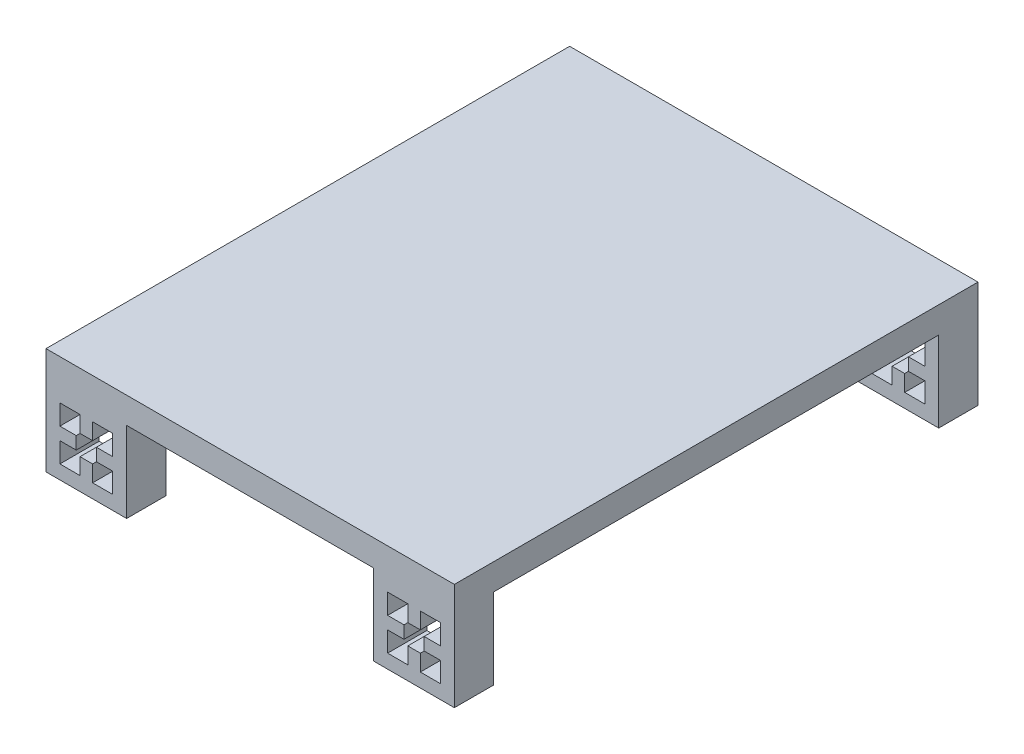
SolidWorks part; units mm, degrees
ref_plane "Plan de face" through (0, 0, 0) normal (0, 0, 1) x (1, 0, 0)
ref_plane "Plan de dessus" through (0, 0, 0) normal (0, 1, 0) x (1, 0, 0)
ref_plane "Plan de droite" through (0, 0, 0) normal (1, 0, 0) x (0, 0, -1)
sketch "Esquisse1" plane through (0, 0, 0) normal (0, 0, 1) x (1, 0, 0)
  line L0 (-30.1176, 6.0342) -> (-30.1176, 10.8342)
  line L1 (-30.1176, 10.8342) -> (-36.3676, 10.8342)
  line L2 (-36.3676, 10.8342) -> (-36.3676, 18.5342)
  line L3 (-36.3676, 18.5342) -> (-28.6676, 18.5342)
  line L4 (-28.6676, 18.5342) -> (-28.6676, 12.2842)
  line L5 (-28.6676, 12.2842) -> (-23.8676, 12.2842)
  line L6 (-23.8676, 18.5342) -> (-23.8676, 12.2842)
  line L7 (-16.1776, 18.5342) -> (-23.8676, 18.5342)
  line L8 (-16.1776, 10.8342) -> (-16.1776, 18.5342)
  line L9 (-22.4276, 10.8342) -> (-16.1776, 10.8342)
  line L10 (-22.4276, 6.0342) -> (-22.4276, 10.8342)
  line L11 (-22.4276, 6.0342) -> (-16.1776, 6.0342)
  line L14 (-30.1176, 6.0342) -> (-36.3676, 6.0342)
  line L15 (-41.6676, 23.8342) -> (-10.8676, 23.8342)
  line L16 (-41.6676, 23.8342) -> (-41.6676, -6.9658)
  line L17 (-10.8676, 23.8342) -> (-10.8676, -6.9658)
  line L29 (-36.3676, 6.0342) -> (-36.3676, -1.6658)
  line L31 (-36.3676, -1.6658) -> (-28.6676, -1.6658)
  line L32 (-28.6676, -1.6658) -> (-28.6676, 4.5842)
  line L34 (-28.6676, 4.5842) -> (-23.8676, 4.5842)
  line L35 (-23.8676, 4.5842) -> (-23.8676, -1.6658)
  line L36 (-23.8676, -1.6658) -> (-16.1776, -1.6658)
  line L37 (-16.1776, -1.6658) -> (-16.1776, 6.0342)
  line L39 (-41.6676, -6.9658) -> (-10.8676, -6.9658)
  dimension "D1" = 30.8
  dimension "D2" = 30.8
  dimension "D3" = 7.7
  dimension "D4" = 6.25
  dimension "D5" = 4.8
extrude "Boss.-Extru.1" add sketch "Esquisse1" along normal blind 15
sketch "Esquisse6" plane through (0, 23.8342, 0) normal (0, 1, 0) x (1, 0, 0)
  line L1 (-41.6676, 185) -> (114.3124, 185)
  line L2 (-41.6676, 185) -> (-41.6676, -15)
  line L3 (-41.6676, -15) -> (114.3124, -15)
  line L4 (114.3124, 185) -> (114.3124, -15)
  line L5 (-41.6676, -15) -> (-41.6676, 0) construction
  line L6 (-10.8676, -15) -> (-41.6676, -15) construction
  dimension "D1" = 155.98
  dimension "D2" = 200
  dimension "D3" = 0
  dimension "D4" = 0
extrude "Boss.-Extru.4" add sketch "Esquisse6" along normal blind 10
sketch "Esquisse16" plane through (0, 0, 15) normal (0, 0, 1) x (1, 0, 0)
  line L0 (95.0624, 6.0342) -> (95.0624, 10.8342)
  line L1 (95.0624, 10.8342) -> (88.8124, 10.8342)
  line L2 (88.8124, 10.8342) -> (88.8124, 18.5342)
  line L3 (88.8124, 18.5342) -> (96.5124, 18.5342)
  line L4 (96.5124, 18.5342) -> (96.5124, 12.2842)
  line L5 (96.5124, 12.2842) -> (101.3124, 12.2842)
  line L6 (101.3124, 18.5342) -> (101.3124, 12.2842)
  line L7 (109.0024, 18.5342) -> (101.3124, 18.5342)
  line L8 (109.0024, 10.8342) -> (109.0024, 18.5342)
  line L9 (102.7524, 10.8342) -> (109.0024, 10.8342)
  line L10 (102.7524, 6.0342) -> (102.7524, 10.8342)
  line L11 (102.7524, 6.0342) -> (109.0024, 6.0342)
  line L14 (95.0624, 6.0342) -> (88.8124, 6.0342)
  line L15 (83.5124, 23.8342) -> (114.3124, 23.8342)
  line L16 (83.5124, 23.8342) -> (83.5124, -6.9658)
  line L17 (114.3124, 23.8342) -> (114.3124, -6.9658)
  line L29 (88.8124, 6.0342) -> (88.8124, -1.6658)
  line L31 (88.8124, -1.6658) -> (96.5124, -1.6658)
  line L32 (96.5124, -1.6658) -> (96.5124, 4.5842)
  line L34 (96.5124, 4.5842) -> (101.3124, 4.5842)
  line L35 (101.3124, 4.5842) -> (101.3124, -1.6658)
  line L36 (101.3124, -1.6658) -> (109.0024, -1.6658)
  line L37 (109.0024, -1.6658) -> (109.0024, 6.0342)
  line L39 (83.5124, -6.9658) -> (114.3124, -6.9658)
  line L41 (-10.8676, 23.8342) -> (114.3124, 23.8342) construction
  line L42 (114.3124, 33.8342) -> (114.3124, 23.8342) construction
  dimension "D1" = 30.8
  dimension "D2" = 30.8
  dimension "D3" = 7.7
  dimension "D4" = 6.25
  dimension "D5" = 4.8
  dimension "D6" = 5.3
  dimension "D7" = 5.3
  dimension "D8" = 0
  dimension "D9" = 0
extrude "Boss.-Extru.12" add sketch "Esquisse16" against normal blind 15
sketch "Esquisse25" plane through (0, 0, -185) normal (0, 0, -1) x (-1, 0, 0)
  line L0 (-102.7624, 6.0342) -> (-102.7624, 10.8342)
  line L1 (-102.7624, 10.8342) -> (-109.0124, 10.8342)
  line L2 (-109.0124, 10.8342) -> (-109.0124, 18.5342)
  line L3 (-109.0124, 18.5342) -> (-101.3124, 18.5342)
  line L4 (-101.3124, 18.5342) -> (-101.3124, 12.2842)
  line L5 (-101.3124, 12.2842) -> (-96.5124, 12.2842)
  line L6 (-96.5124, 18.5342) -> (-96.5124, 12.2842)
  line L7 (-88.8224, 18.5342) -> (-96.5124, 18.5342)
  line L8 (-88.8224, 10.8342) -> (-88.8224, 18.5342)
  line L9 (-95.0724, 10.8342) -> (-88.8224, 10.8342)
  line L10 (-95.0724, 6.0342) -> (-95.0724, 10.8342)
  line L11 (-95.0724, 6.0342) -> (-88.8224, 6.0342)
  line L14 (-102.7624, 6.0342) -> (-109.0124, 6.0342)
  line L15 (-114.3124, 23.8342) -> (-83.5124, 23.8342)
  line L16 (-114.3124, 23.8342) -> (-114.3124, -6.9658)
  line L17 (-83.5124, 23.8342) -> (-83.5124, -6.9658)
  line L29 (-109.0124, 6.0342) -> (-109.0124, -1.6658)
  line L31 (-109.0124, -1.6658) -> (-101.3124, -1.6658)
  line L32 (-101.3124, -1.6658) -> (-101.3124, 4.5842)
  line L34 (-101.3124, 4.5842) -> (-96.5124, 4.5842)
  line L35 (-96.5124, 4.5842) -> (-96.5124, -1.6658)
  line L36 (-96.5124, -1.6658) -> (-88.8224, -1.6658)
  line L37 (-88.8224, -1.6658) -> (-88.8224, 6.0342)
  line L39 (-114.3124, -6.9658) -> (-83.5124, -6.9658)
  line L40 (-114.3124, 23.8342) -> (41.6676, 23.8342) construction
  line L41 (-114.3124, 33.8342) -> (-114.3124, 23.8342) construction
  dimension "D1" = 30.8
  dimension "D2" = 30.8
  dimension "D3" = 7.7
  dimension "D4" = 6.25
  dimension "D5" = 4.8
  dimension "D6" = 5.3
  dimension "D7" = 5.3
  dimension "D8" = 0
  dimension "D9" = 0
extrude "Boss.-Extru.21" add sketch "Esquisse25" against normal blind 15
sketch "Esquisse26" plane through (0, 0, -185) normal (0, 0, -1) x (-1, 0, 0)
  line L0 (22.4176, 6.0342) -> (22.4176, 10.8342)
  line L1 (22.4176, 10.8342) -> (16.1676, 10.8342)
  line L2 (16.1676, 10.8342) -> (16.1676, 18.5342)
  line L3 (16.1676, 18.5342) -> (23.8676, 18.5342)
  line L4 (23.8676, 18.5342) -> (23.8676, 12.2842)
  line L5 (23.8676, 12.2842) -> (28.6676, 12.2842)
  line L6 (28.6676, 18.5342) -> (28.6676, 12.2842)
  line L7 (36.3576, 18.5342) -> (28.6676, 18.5342)
  line L8 (36.3576, 10.8342) -> (36.3576, 18.5342)
  line L9 (30.1076, 10.8342) -> (36.3576, 10.8342)
  line L10 (30.1076, 6.0342) -> (30.1076, 10.8342)
  line L11 (30.1076, 6.0342) -> (36.3576, 6.0342)
  line L14 (22.4176, 6.0342) -> (16.1676, 6.0342)
  line L15 (10.8676, 23.8342) -> (41.6676, 23.8342)
  line L16 (10.8676, 23.8342) -> (10.8676, -6.9658)
  line L17 (41.6676, 23.8342) -> (41.6676, -6.9658)
  line L29 (16.1676, 6.0342) -> (16.1676, -1.6658)
  line L31 (16.1676, -1.6658) -> (23.8676, -1.6658)
  line L32 (23.8676, -1.6658) -> (23.8676, 4.5842)
  line L34 (23.8676, 4.5842) -> (28.6676, 4.5842)
  line L35 (28.6676, 4.5842) -> (28.6676, -1.6658)
  line L36 (28.6676, -1.6658) -> (36.3576, -1.6658)
  line L37 (36.3576, -1.6658) -> (36.3576, 6.0342)
  line L39 (10.8676, -6.9658) -> (41.6676, -6.9658)
  line L40 (10.8676, 23.8342) -> (41.6676, 23.8342) construction
  line L41 (41.6676, 33.8342) -> (41.6676, 23.8342) construction
  dimension "D1" = 30.8
  dimension "D2" = 30.8
  dimension "D3" = 7.7
  dimension "D4" = 6.25
  dimension "D5" = 4.8
  dimension "D6" = 5.3
  dimension "D7" = 5.3
  dimension "D8" = 0
  dimension "D9" = 0
extrude "Boss.-Extru.22" add sketch "Esquisse26" against normal blind 15
